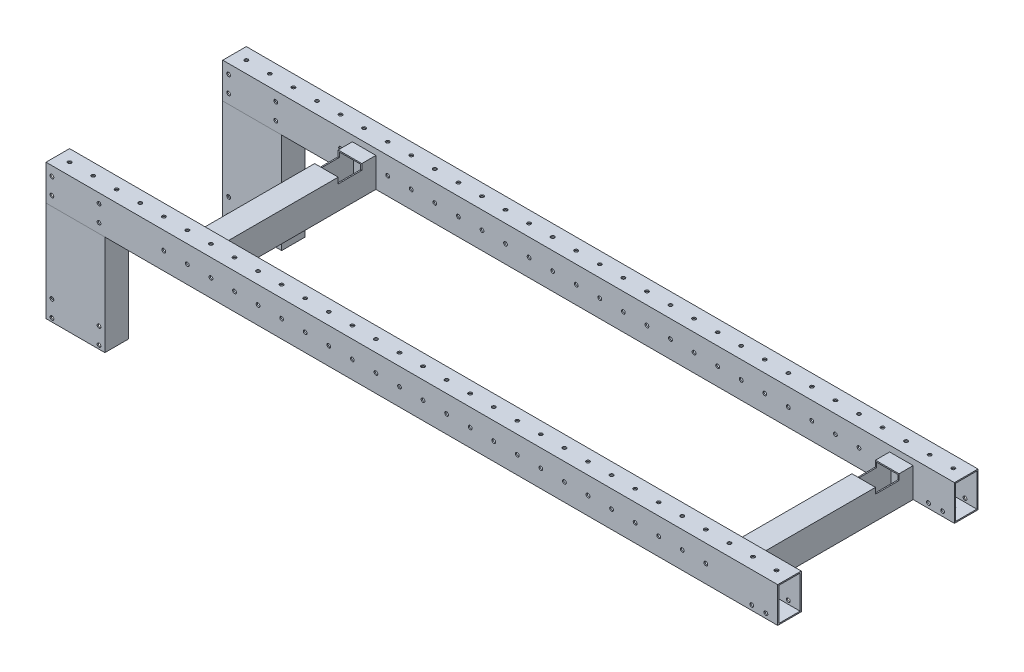
SolidWorks part; units mm, degrees
material "6061-T6 (SS)"
ref_plane "前视基准面" through (0, 0, 0) normal (0, 0, 1) x (1, 0, 0)
ref_plane "上视基准面" through (0, 0, 0) normal (0, 1, 0) x (1, 0, 0)
ref_plane "右视基准面" through (0, 0, 0) normal (1, 0, 0) x (0, 0, -1)
sketch3d "3D草图1"
  line L0 (0, 0, -179.0514) -> (0, 0, 210.5605) construction
  line L1 (-429.4613, 0, 0) -> (512.3941, 0, 0) construction
  line L2 (0, 0, 75) -> (621, 0, 75)
  line L3 (120, 0, 75) -> (120, 0, -75) construction
  line L4 (0, 0, -75) -> (621, 0, -75)
  point P12 (120, 0, 0)
  dimension "D1" = 621
  dimension "D2" = 150
other "方形管 20 X 20 X 2(1)"
ref_plane "基准面1" through (0, 0, 75) normal (1, 0, 0) x (0, 0, -1)
sketch "Sketch1" plane through (0, 0, 75) normal (1, 0, 0) x (0, 0, -1)
  line L0 (9, 14) -> (9, -14)
  line L1 (10, 15) -> (-10, 15)
  line L2 (10, 15) -> (10, -15)
  line L3 (10, -15) -> (-10, -15)
  line L4 (-10, 15) -> (-10, -15)
  line L5 (10, 15) -> (-10, -15) construction
  line L6 (10, -15) -> (-10, 15) construction
  line L7 (9, -14) -> (-9, -14)
  line L8 (-9, 14) -> (-9, -14)
  line L9 (9, 14) -> (-9, 14)
  point P0 (0, 0)
  dimension "D1" = 1
  dimension "D2" = 20
  dimension "D3" = 30
sketch "草图3" plane through (0, 0, 85) normal (0, 0, 1) x (1, 0, 0)
  line L0 (621, 0) -> (529.9491, 0) construction
  line L1 (621, 15) -> (621, -15) construction
  line L2 (5, 7) -> (45, 7) construction
  line L3 (25, 7) -> (25, -12.2961) construction
  line L4 (0, -15) -> (0, 15) construction
  circle A0 centre (45, 7) radius 1.6
  circle A1 centre (5, 7) radius 1.6
  circle A2 centre (45, -7) radius 1.6
  circle A3 centre (5, -7) radius 1.6
  dimension "D1" = 3.2
  dimension "D2" = 14
  dimension "D3" = 25
  dimension "D4" = 40
extrude "切除-拉伸1" cut sketch "草图3" against normal through all
sketch "草图5" plane through (0, 15, 0) normal (0, 1, 0) x (1, 0, 0)
  line L0 (684.2067, 0) -> (-96.6882, 0) construction
  line L1 (0, -75) -> (130.4676, -75) construction
  line L2 (0, -65) -> (0, -85) construction
  line L3 (10, 75) -> (30, 75) construction
  circle A0 centre (10, -75) radius 1.5
  circle A1 centre (10, 75) radius 1.5
  circle A2 centre (30, 75) radius 1.5
  circle A3 centre (30, -75) radius 1.5
  circle A4 centre (50, 75) radius 1.5
  circle A5 centre (50, -75) radius 1.5
  circle A6 centre (70, 75) radius 1.5
  circle A7 centre (70, -75) radius 1.5
  circle A8 centre (90, 75) radius 1.5
  circle A9 centre (90, -75) radius 1.5
  circle A10 centre (110, 75) radius 1.5
  circle A11 centre (110, -75) radius 1.5
  circle A12 centre (130, 75) radius 1.5
  circle A13 centre (130, -75) radius 1.5
  circle A14 centre (150, 75) radius 1.5
  circle A15 centre (150, -75) radius 1.5
  circle A16 centre (170, 75) radius 1.5
  circle A17 centre (170, -75) radius 1.5
  circle A18 centre (190, 75) radius 1.5
  circle A19 centre (190, -75) radius 1.5
  circle A20 centre (210, 75) radius 1.5
  circle A21 centre (210, -75) radius 1.5
  circle A22 centre (230, 75) radius 1.5
  circle A23 centre (230, -75) radius 1.5
  circle A24 centre (250, 75) radius 1.5
  circle A25 centre (250, -75) radius 1.5
  circle A26 centre (270, 75) radius 1.5
  circle A27 centre (270, -75) radius 1.5
  circle A28 centre (290, 75) radius 1.5
  circle A29 centre (290, -75) radius 1.5
  circle A30 centre (310, 75) radius 1.5
  circle A31 centre (310, -75) radius 1.5
  circle A32 centre (330, 75) radius 1.5
  circle A33 centre (330, -75) radius 1.5
  circle A34 centre (350, 75) radius 1.5
  circle A35 centre (350, -75) radius 1.5
  circle A36 centre (370, 75) radius 1.5
  circle A37 centre (370, -75) radius 1.5
  circle A38 centre (390, 75) radius 1.5
  circle A39 centre (390, -75) radius 1.5
  circle A40 centre (410, 75) radius 1.5
  circle A41 centre (410, -75) radius 1.5
  circle A42 centre (430, 75) radius 1.5
  circle A43 centre (430, -75) radius 1.5
  circle A44 centre (450, 75) radius 1.5
  circle A45 centre (450, -75) radius 1.5
  circle A46 centre (470, 75) radius 1.5
  circle A47 centre (470, -75) radius 1.5
  circle A48 centre (490, 75) radius 1.5
  circle A49 centre (490, -75) radius 1.5
  circle A50 centre (510, 75) radius 1.5
  circle A51 centre (510, -75) radius 1.5
  circle A52 centre (530, 75) radius 1.5
  circle A53 centre (530, -75) radius 1.5
  circle A54 centre (550, 75) radius 1.5
  circle A55 centre (550, -75) radius 1.5
  circle A56 centre (570, 75) radius 1.5
  circle A57 centre (570, -75) radius 1.5
  circle A58 centre (590, 75) radius 1.5
  circle A59 centre (590, -75) radius 1.5
  circle A60 centre (610, 75) radius 1.5
  circle A61 centre (610, -75) radius 1.5
  dimension "D1" = 3
  dimension "D2" = 10
  dimension "D4" = 20
  dimension "D3" = 31
extrude "切除-拉伸3" cut sketch "草图5" against normal through all
sketch "草图6" plane through (0, 0, 85) normal (0, 0, 1) x (1, 0, 0)
  line L0 (5, 7) -> (45, 7) construction
  line L1 (25, 7) -> (25, 0) construction
  line L3 (25, 0) -> (621, 0) construction
  line L4 (621, 15) -> (621, -15) construction
  line L5 (25, 0) -> (620.6369, -20.8001) construction
  line L6 (25.5238, 15) -> (621.1607, -5.8001) construction
  line L7 (25.5238, 15) -> (24.4762, -15) construction
  line L8 (621.1607, -5.8001) -> (620.1131, -35.8001) construction
  line L9 (24.4762, -15) -> (620.1131, -35.8001) construction
  line L10 (25.5238, 15) -> (620.1131, -35.8001) construction
  line L11 (621.1607, -5.8001) -> (24.4762, -15) construction
  line L12 (25, 0) -> (620.9092, -10.4016) construction
  circle A0 centre (611, 0) radius 1.6 construction
  circle A1 centre (599, 0) radius 1.6 construction
  circle A2 centre (599, -11) radius 1.6
  circle A3 centre (611, -11) radius 1.6
  point P11 (322.8185, -10.4001)
  dimension "D4" = 3.2
  dimension "D7" = 4
  dimension "D1" = 2
  dimension "D2" = 30
  dimension "D3" = 1
  dimension "D5" = 10
  dimension "D6" = 12
sketch "草图8" plane through (0, 0, 65) normal (0, 0, -1) x (-1, 0, 0)
  line L0 (-621, -15) -> (0, -15) construction
  line L1 (-586, 10) -> (-566, 10)
  line L2 (-586, 10) -> (-586, -15)
  line L3 (-586, -15) -> (-566, -15)
  line L4 (-566, 10) -> (-566, -15)
  line L5 (-586, 10) -> (-566, -15) construction
  line L6 (-586, -15) -> (-566, 10) construction
  line L7 (-585, 9) -> (-567, 9)
  line L8 (-567, 9) -> (-567, -14)
  line L9 (-585, -14) -> (-567, -14)
  line L10 (-585, 9) -> (-585, -14)
  line L11 (-621, -15) -> (-621, 15) construction
  point P0 (-576, -2.5)
  dimension "D1" = 25
  dimension "D2" = 20
  dimension "D4" = 35
  dimension "D3" = 1
extrude "凸台-拉伸1" add sketch "草图8" along normal up to next separate body
sketch "草图9" plane through (586, 0, 0) normal (1, 0, 0) x (0, 0, -1)
  line L0 (65, 10) -> (-65, 10) construction
  line L1 (33, 5) -> (53, 5)
  line L2 (33, 5) -> (33, 10)
  line L3 (33, 10) -> (53, 10)
  line L4 (53, 5) -> (53, 10)
  line L5 (33, 5) -> (53, 10) construction
  line L6 (33, 10) -> (53, 5) construction
  line L7 (65, 10) -> (65, -15) construction
  point P0 (43, 7.5)
  dimension "D1" = 22
  dimension "D2" = 20
  dimension "D3" = 5
extrude "切除-拉伸4" cut sketch "草图9" against normal up to surface (20 mm away) up to face at (566, -2.5, 0)
extrude "切除-拉伸5" cut sketch "草图6" against normal through all
sketch "草图10" plane through (0, -15, 0) normal (0, -1, 0) x (1, 0, 0)
  line L0 (621, 65) -> (0, 65) construction
  line L1 (0, 85) -> (50, 85)
  line L2 (0, 85) -> (0, 65)
  line L3 (0, 65) -> (50, 65)
  line L4 (50, 85) -> (50, 65)
  line L5 (1, 84) -> (1, 66)
  line L6 (1, 66) -> (49, 66)
  line L7 (49, 84) -> (49, 66)
  line L8 (1, 84) -> (49, 84)
  dimension "D1" = 50
  dimension "D2" = 1
extrude "凸台-拉伸2" add sketch "草图10" along normal blind 85 separate body
sketch "草图11" plane through (0, 0, 85) normal (0, 0, 1) x (1, 0, 0)
  line L0 (25, -100) -> (25, -15) construction
  line L1 (50, -100) -> (0, -100) construction
  line L2 (621, -15) -> (0, -15) construction
  line L3 (0, -90) -> (50, -90) construction
  line L4 (0, -100) -> (0, -15) construction
  line L5 (50, -100) -> (50, -15) construction
  line L6 (0, 0) -> (60.7939, 0) construction
  line L7 (0, 15) -> (0, -15) construction
  circle A0 centre (45, -83) radius 1.6
  circle A1 centre (45, -97) radius 1.6
  circle A2 centre (5, -97) radius 1.6
  circle A3 centre (5, -83) radius 1.6
  dimension "D2" = 40
  dimension "D4" = 3.2
  dimension "D1" = 10
  dimension "D3" = 14
extrude "切除-拉伸6" cut sketch "草图11" against normal through all
mirror "镜向1" about plane through (0, 0, 0) normal (0, 0, 1) of bodies 120
pattern_linear "阵列(线性)1" count 2 spacing 456 along (-1, 0, 0) of bodies 116
sketch "草图12" plane through (0, 0, 85) normal (0, 0, 1) x (1, 0, 0)
  line L0 (0, 0) -> (621, 0) construction
  line L1 (621, 15) -> (621, -15) construction
  line L2 (100, 0) -> (120, 0) construction
  line L3 (0, 15) -> (0, -15) construction
  circle A0 centre (100, 0) radius 1.6
  circle A1 centre (120, 0) radius 1.6
  circle A2 centre (140, 0) radius 1.6
  circle A3 centre (160, 0) radius 1.6
  circle A4 centre (180, 0) radius 1.6
  circle A5 centre (200, 0) radius 1.6
  circle A6 centre (220, 0) radius 1.6
  circle A7 centre (240, 0) radius 1.6
  circle A8 centre (260, 0) radius 1.6
  circle A9 centre (280, 0) radius 1.6
  circle A10 centre (300, 0) radius 1.6
  circle A11 centre (320, 0) radius 1.6
  circle A12 centre (340, 0) radius 1.6
  circle A13 centre (360, 0) radius 1.6
  circle A14 centre (380, 0) radius 1.6
  circle A15 centre (400, 0) radius 1.6
  circle A16 centre (420, 0) radius 1.6
  circle A17 centre (440, 0) radius 1.6
  circle A18 centre (460, 0) radius 1.6
  circle A19 centre (480, 0) radius 1.6
  circle A20 centre (500, 0) radius 1.6
  circle A21 centre (520, 0) radius 1.6
  circle A22 centre (540, 0) radius 1.6
  circle A23 centre (560, 0) radius 1.6
  dimension "D1" = 3.2
  dimension "D3" = 20
  dimension "D4" = 100
  dimension "D2" = 24
extrude "切除-拉伸7" cut sketch "草图12" against normal through all
sketch "草图13" plane through (0, 15, 0) normal (0, 1, 0) x (1, 0, 0)
  line L0 (566, 65) -> (586, 65) construction
  line L1 (566, 65) -> (586, 65) construction
  line L2 (581, 65) -> (571, 65) construction
  line L3 (581, 55) -> (571, 55)
  line L4 (581, 75) -> (571, 75)
  line L5 (110, 65) -> (130, 65) construction
  line L6 (110, 65) -> (130, 65) construction
  line L7 (125, 65) -> (115, 65) construction
  line L8 (125, 56) -> (115, 56)
  line L9 (125, 74) -> (115, 74)
  line L10 (621, 65) -> (0, 65) construction
  line L11 (546, 61) -> (526, 61)
  line L12 (546, 61) -> (546, 65)
  line L13 (546, 65) -> (526, 65)
  line L14 (526, 61) -> (526, 65)
  line L15 (546, 61) -> (526, 65) construction
  line L16 (546, 65) -> (526, 61) construction
  line L17 (566, 33) -> (566, -65) construction
  line L18 (426, 61) -> (426, 65)
  line L19 (426, 61) -> (406, 61)
  line L20 (406, 61) -> (406, 65)
  line L21 (426, 65) -> (406, 65)
  line L22 (306, 61) -> (306, 65)
  line L23 (306, 61) -> (286, 61)
  line L24 (286, 61) -> (286, 65)
  line L25 (306, 65) -> (286, 65)
  line L26 (186, 61) -> (186, 65)
  line L27 (186, 61) -> (166, 61)
  line L28 (166, 61) -> (166, 65)
  line L29 (186, 65) -> (166, 65)
  line L30 (546, 61) -> (426, 61) construction
  line L31 (674.0035, 0) -> (0, 0) construction
  line L32 (621, 85) -> (621, 65) construction
  line L33 (616, 61) -> (606, 61)
  line L34 (616, 61) -> (616, 65)
  line L35 (616, 65) -> (606, 65)
  line L36 (606, 61) -> (606, 65)
  line L37 (616, 61) -> (606, 65) construction
  line L38 (616, 65) -> (606, 61) construction
  line L39 (0, 85) -> (0, 65) construction
  line L40 (30, 61) -> (20, 61)
  line L41 (30, 61) -> (30, 65)
  line L42 (30, 65) -> (20, 65)
  line L43 (20, 61) -> (20, 65)
  line L44 (30, 61) -> (20, 65) construction
  line L45 (30, 65) -> (20, 61) construction
  line L46 (621, 85) -> (0, 85) construction
  line L47 (621, 85) -> (0, 85)
  line L48 (0, 85) -> (0, -85)
  line L49 (621, 85) -> (621, -85)
  line L50 (30, -65) -> (20, -61) construction
  line L51 (30, -61) -> (20, -65) construction
  line L52 (616, -65) -> (606, -61) construction
  line L53 (616, -61) -> (606, -65) construction
  line L54 (546, -61) -> (426, -61) construction
  line L55 (546, -65) -> (526, -61) construction
  line L56 (546, -61) -> (526, -65) construction
  line L57 (110, -65) -> (130, -65) construction
  line L58 (566, -65) -> (586, -65) construction
  line L59 (621, -85) -> (0, -85)
  line L60 (20, -61) -> (20, -65)
  line L61 (30, -65) -> (20, -65)
  line L62 (30, -61) -> (30, -65)
  line L63 (30, -61) -> (20, -61)
  line L64 (606, -61) -> (606, -65)
  line L65 (616, -65) -> (606, -65)
  line L66 (616, -61) -> (616, -65)
  line L67 (616, -61) -> (606, -61)
  line L68 (186, -65) -> (166, -65)
  line L69 (166, -61) -> (166, -65)
  line L70 (186, -61) -> (166, -61)
  line L71 (186, -61) -> (186, -65)
  line L72 (306, -65) -> (286, -65)
  line L73 (286, -61) -> (286, -65)
  line L74 (306, -61) -> (286, -61)
  line L75 (306, -61) -> (306, -65)
  line L76 (426, -65) -> (406, -65)
  line L77 (406, -61) -> (406, -65)
  line L78 (426, -61) -> (406, -61)
  line L79 (426, -61) -> (426, -65)
  line L80 (526, -61) -> (526, -65)
  line L81 (546, -65) -> (526, -65)
  line L82 (546, -61) -> (546, -65)
  line L83 (546, -61) -> (526, -61)
  line L84 (125, -65) -> (115, -65) construction
  line L85 (125, -56) -> (115, -56)
  line L86 (125, -74) -> (115, -74)
  line L87 (581, -65) -> (571, -65) construction
  line L88 (581, -55) -> (571, -55)
  line L89 (581, -75) -> (571, -75)
  line L90 (576, 65) -> (576, 27.064) construction
  line L91 (590, 52) -> (586, 52)
  line L92 (590, 52) -> (590, 40)
  line L93 (590, 40) -> (586, 40)
  line L94 (586, 52) -> (586, 40)
  line L95 (590, 52) -> (586, 40) construction
  line L96 (590, 40) -> (586, 52) construction
  line L97 (562, 40) -> (566, 40)
  line L98 (566, 52) -> (566, 40)
  line L99 (562, 52) -> (566, 52)
  line L100 (562, 52) -> (562, 40)
  line L101 (562, -52) -> (562, -40)
  line L102 (562, -52) -> (566, -52)
  line L103 (566, -52) -> (566, -40)
  line L104 (562, -40) -> (566, -40)
  line L105 (590, -40) -> (586, -40)
  line L106 (586, -52) -> (586, -40)
  line L107 (590, -52) -> (586, -52)
  line L108 (590, -52) -> (590, -40)
  line L109 (134, 52) -> (134, 40)
  line L110 (134, 52) -> (130, 52)
  line L111 (130, 52) -> (130, 40)
  line L112 (134, 40) -> (130, 40)
  line L113 (106, 40) -> (110, 40)
  line L114 (110, 52) -> (110, 40)
  line L115 (106, 52) -> (110, 52)
  line L116 (106, 52) -> (106, 40)
  line L117 (134, -40) -> (130, -40)
  line L118 (130, -52) -> (130, -40)
  line L119 (134, -52) -> (130, -52)
  line L120 (134, -52) -> (134, -40)
  line L121 (106, -52) -> (106, -40)
  line L122 (106, -40) -> (110, -40)
  line L123 (110, -52) -> (110, -40)
  line L124 (106, -52) -> (110, -52)
  line L125 (590, 52) -> (134, 52) construction
  arc A0 (581, 55) -> (581, 75) centre (581, 65) ccw
  circle A1 centre (610, 75) radius 1.5
  circle A2 centre (610, 75) radius 1.5
  circle A3 centre (590, 75) radius 1.5
  circle A4 centre (590, 75) radius 1.5
  circle A5 centre (570, 75) radius 1.5
  circle A6 centre (570, 75) radius 1.5 construction
  circle A7 centre (550, 75) radius 1.5
  circle A8 centre (550, 75) radius 1.5
  circle A9 centre (530, 75) radius 1.5
  circle A10 centre (530, 75) radius 1.5
  circle A11 centre (510, 75) radius 1.5
  circle A12 centre (510, 75) radius 1.5
  circle A13 centre (490, 75) radius 1.5
  circle A14 centre (490, 75) radius 1.5
  circle A15 centre (470, 75) radius 1.5
  circle A16 centre (470, 75) radius 1.5
  circle A17 centre (450, 75) radius 1.5
  circle A18 centre (450, 75) radius 1.5
  circle A19 centre (430, 75) radius 1.5
  circle A20 centre (430, 75) radius 1.5
  circle A21 centre (410, 75) radius 1.5
  circle A22 centre (410, 75) radius 1.5
  circle A23 centre (390, 75) radius 1.5
  circle A24 centre (390, 75) radius 1.5
  circle A25 centre (370, 75) radius 1.5
  circle A26 centre (370, 75) radius 1.5
  circle A27 centre (350, 75) radius 1.5
  circle A28 centre (350, 75) radius 1.5
  circle A29 centre (330, 75) radius 1.5
  circle A30 centre (330, 75) radius 1.5
  circle A31 centre (310, 75) radius 1.5
  circle A32 centre (310, 75) radius 1.5
  circle A33 centre (290, 75) radius 1.5
  circle A34 centre (290, 75) radius 1.5
  circle A35 centre (270, 75) radius 1.5
  circle A36 centre (270, 75) radius 1.5
  circle A37 centre (250, 75) radius 1.5
  circle A38 centre (250, 75) radius 1.5
  circle A39 centre (230, 75) radius 1.5
  circle A40 centre (230, 75) radius 1.5
  circle A41 centre (210, 75) radius 1.5
  circle A42 centre (210, 75) radius 1.5
  circle A43 centre (190, 75) radius 1.5
  circle A44 centre (190, 75) radius 1.5
  circle A45 centre (170, 75) radius 1.5
  circle A46 centre (170, 75) radius 1.5
  circle A47 centre (150, 75) radius 1.5
  circle A48 centre (150, 75) radius 1.5
  circle A49 centre (130, 75) radius 1.5
  circle A50 centre (130, 75) radius 1.5
  circle A51 centre (110, 75) radius 1.5
  circle A52 centre (110, 75) radius 1.5
  circle A53 centre (90, 75) radius 1.5
  circle A54 centre (90, 75) radius 1.5
  circle A55 centre (70, 75) radius 1.5
  circle A56 centre (70, 75) radius 1.5
  circle A57 centre (50, 75) radius 1.5
  circle A58 centre (50, 75) radius 1.5
  circle A59 centre (30, 75) radius 1.5
  circle A60 centre (30, 75) radius 1.5
  circle A61 centre (10, 75) radius 1.5
  circle A62 centre (10, 75) radius 1.5
  circle A63 centre (610, -75) radius 1.5
  circle A64 centre (610, -75) radius 1.5
  circle A65 centre (590, -75) radius 1.5
  circle A66 centre (590, -75) radius 1.5
  circle A67 centre (570, -75) radius 1.5
  circle A68 centre (570, -75) radius 1.5 construction
  circle A69 centre (550, -75) radius 1.5
  circle A70 centre (550, -75) radius 1.5
  circle A71 centre (530, -75) radius 1.5
  circle A72 centre (530, -75) radius 1.5
  circle A73 centre (510, -75) radius 1.5
  circle A74 centre (510, -75) radius 1.5
  circle A75 centre (490, -75) radius 1.5
  circle A76 centre (490, -75) radius 1.5
  circle A77 centre (470, -75) radius 1.5
  circle A78 centre (470, -75) radius 1.5
  circle A79 centre (450, -75) radius 1.5
  circle A80 centre (450, -75) radius 1.5
  circle A81 centre (430, -75) radius 1.5
  circle A82 centre (430, -75) radius 1.5
  circle A83 centre (410, -75) radius 1.5
  circle A84 centre (410, -75) radius 1.5
  circle A85 centre (390, -75) radius 1.5
  circle A86 centre (390, -75) radius 1.5
  circle A87 centre (370, -75) radius 1.5
  circle A88 centre (370, -75) radius 1.5
  circle A89 centre (350, -75) radius 1.5
  circle A90 centre (350, -75) radius 1.5
  circle A91 centre (330, -75) radius 1.5
  circle A92 centre (330, -75) radius 1.5
  circle A93 centre (310, -75) radius 1.5
  circle A94 centre (310, -75) radius 1.5
  circle A95 centre (290, -75) radius 1.5
  circle A96 centre (290, -75) radius 1.5
  circle A97 centre (270, -75) radius 1.5
  circle A98 centre (270, -75) radius 1.5
  circle A99 centre (250, -75) radius 1.5
  circle A100 centre (250, -75) radius 1.5
  circle A101 centre (230, -75) radius 1.5
  circle A102 centre (230, -75) radius 1.5
  circle A103 centre (210, -75) radius 1.5
  circle A104 centre (210, -75) radius 1.5
  circle A105 centre (190, -75) radius 1.5
  circle A106 centre (190, -75) radius 1.5
  circle A107 centre (170, -75) radius 1.5
  circle A108 centre (170, -75) radius 1.5
  circle A109 centre (150, -75) radius 1.5
  circle A110 centre (150, -75) radius 1.5
  circle A111 centre (130, -75) radius 1.5
  circle A112 centre (130, -75) radius 1.5
  circle A113 centre (110, -75) radius 1.5
  circle A114 centre (110, -75) radius 1.5
  circle A115 centre (90, -75) radius 1.5
  circle A116 centre (90, -75) radius 1.5
  circle A117 centre (70, -75) radius 1.5
  circle A118 centre (70, -75) radius 1.5
  circle A119 centre (50, -75) radius 1.5
  circle A120 centre (50, -75) radius 1.5
  circle A121 centre (30, -75) radius 1.5
  circle A122 centre (30, -75) radius 1.5
  circle A123 centre (10, -75) radius 1.5
  circle A124 centre (10, -75) radius 1.5
  arc A125 (571, 75) -> (571, 55) centre (571, 65) ccw
  arc A126 (125, 56) -> (125, 74) centre (125, 65) ccw
  arc A127 (115, 74) -> (115, 56) centre (115, 65) ccw
  circle A128 centre (570, -75) radius 1.5 construction
  circle A129 centre (10, -75) radius 1.5
  circle A130 centre (30, -75) radius 1.5
  circle A131 centre (50, -75) radius 1.5
  circle A132 centre (70, -75) radius 1.5
  circle A133 centre (90, -75) radius 1.5
  circle A134 centre (110, -75) radius 1.5
  circle A135 centre (130, -75) radius 1.5
  circle A136 centre (150, -75) radius 1.5
  circle A137 centre (170, -75) radius 1.5
  circle A138 centre (190, -75) radius 1.5
  circle A139 centre (210, -75) radius 1.5
  circle A140 centre (230, -75) radius 1.5
  circle A141 centre (250, -75) radius 1.5
  circle A142 centre (270, -75) radius 1.5
  circle A143 centre (290, -75) radius 1.5
  circle A144 centre (310, -75) radius 1.5
  circle A145 centre (330, -75) radius 1.5
  circle A146 centre (350, -75) radius 1.5
  circle A147 centre (370, -75) radius 1.5
  circle A148 centre (390, -75) radius 1.5
  circle A149 centre (410, -75) radius 1.5
  circle A150 centre (430, -75) radius 1.5
  circle A151 centre (450, -75) radius 1.5
  circle A152 centre (470, -75) radius 1.5
  circle A153 centre (490, -75) radius 1.5
  circle A154 centre (510, -75) radius 1.5
  circle A155 centre (530, -75) radius 1.5
  circle A156 centre (550, -75) radius 1.5
  circle A157 centre (590, -75) radius 1.5
  circle A158 centre (610, -75) radius 1.5
  arc A159 (125, -56) -> (125, -74) centre (125, -65) cw
  arc A160 (115, -74) -> (115, -56) centre (115, -65) cw
  arc A161 (581, -55) -> (581, -75) centre (581, -65) cw
  arc A162 (571, -75) -> (571, -55) centre (571, -65) cw
  point P190 (576, 65)
  point P199 (120, 65)
  point P204 (536, 63)
  point P230 (611, 63)
  point P237 (25, 63)
  point P296 (621, 0)
  point P308 (25, -63)
  point P309 (611, -63)
  point P310 (536, -63)
  point P313 (120, -65)
  point P320 (576, -65)
  point P325 (588, 46)
  dimension "D63" = 20
  dimension "D64" = 10
  dimension "D65" = 18
  dimension "D66" = 10
  dimension "D67" = 4
  dimension "D68" = 20
  dimension "D69" = 20
  dimension "D71" = 120
  dimension "D72" = 10
  dimension "D73" = 5
  dimension "D74" = 10
  dimension "D75" = 20
  dimension "D76" = 4
  dimension "D77" = 12
  dimension "D78" = 40
  dimension "D79" = 2
  dimension "D80" = 456
  dimension "D1" = 0
  dimension "D2" = 0
  dimension "D3" = 0
  dimension "D4" = 0
  dimension "D5" = 0
  dimension "D6" = 0
  dimension "D7" = 0
  dimension "D8" = 0
  dimension "D9" = 0
  dimension "D10" = 0
  dimension "D11" = 0
  dimension "D12" = 0
  dimension "D13" = 0
  dimension "D14" = 0
  dimension "D15" = 0
  dimension "D16" = 0
  dimension "D17" = 0
  dimension "D18" = 0
  dimension "D19" = 0
  dimension "D20" = 0
  dimension "D21" = 0
  dimension "D22" = 0
  dimension "D23" = 0
  dimension "D24" = 0
  dimension "D25" = 0
  dimension "D26" = 0
  dimension "D27" = 0
  dimension "D28" = 0
  dimension "D29" = 0
  dimension "D30" = 0
  dimension "D31" = 0
  dimension "D32" = 0
  dimension "D33" = 0
  dimension "D34" = 0
  dimension "D35" = 0
  dimension "D36" = 0
  dimension "D37" = 0
  dimension "D38" = 0
  dimension "D39" = 0
  dimension "D40" = 0
  dimension "D41" = 0
  dimension "D42" = 0
  dimension "D43" = 0
  dimension "D44" = 0
  dimension "D45" = 0
  dimension "D46" = 0
  dimension "D47" = 0
  dimension "D48" = 0
  dimension "D49" = 0
  dimension "D50" = 0
  dimension "D51" = 0
  dimension "D52" = 0
  dimension "D53" = 0
  dimension "D54" = 0
  dimension "D55" = 0
  dimension "D56" = 0
  dimension "D57" = 0
  dimension "D58" = 0
  dimension "D59" = 0
  dimension "D60" = 0
  dimension "D61" = 0
  dimension "D62" = 0
  dimension "D70" = 4
extrude "凸台-拉伸3" [suppressed] add sketch "草图13" along normal blind 2 separate body
sketch "草图14" [suppressed] plane through (0, 0, 85) normal (0, 0, 1) x (1, 0, 0)
  line L0 (0, -100) -> (50, -100)
  line L1 (50, -100) -> (135, -15)
  line L2 (621, -15) -> (0, -15) construction
  line L3 (135, -15) -> (135, 15)
  line L4 (0, 15) -> (621, 15) construction
  line L5 (135, 15) -> (0, 15)
  line L6 (0, 15) -> (0, -100)
  line L7 (50, -15) -> (0, -15) construction
  line L8 (-10, 0) -> (60, 0)
  line L9 (-10, 0) -> (-10, -30)
  line L10 (-10, -30) -> (60, -30)
  line L11 (60, 0) -> (60, -30)
  line L12 (-10, 0) -> (60, -30) construction
  line L13 (-10, -30) -> (60, 0) construction
  line L14 (0, 15) -> (-15, 0)
  line L15 (-15, 0) -> (-15, -30)
  line L16 (-15, -30) -> (0, -45)
  circle A0 centre (5, 7) radius 1.6 construction
  circle A1 centre (5, 7) radius 1.6
  circle A2 centre (45, 7) radius 1.6 construction
  circle A3 centre (45, 7) radius 1.6
  circle A4 centre (5, -97) radius 1.6 construction
  circle A5 centre (5, -97) radius 1.6
  circle A6 centre (45, -97) radius 1.6 construction
  circle A7 centre (45, -97) radius 1.6
  circle A8 centre (120, 0) radius 1.6 construction
  circle A9 centre (120, 0) radius 1.6
  point P27 (25, -15)
  circle M12 centre (5, -83) radius 1.6
  circle M13 centre (5, -97) radius 1.6
  circle M14 centre (45, -97) radius 1.6
  circle M15 centre (45, -83) radius 1.6
  line M17 (0, -15) -> (0, -100)
  line M18 (0, -100) -> (50, -100)
  line M19 (50, -100) -> (50, -15)
  dimension "D1" = 45
  dimension "D2" = 70
  dimension "D3" = 30
  dimension "D4" = 45
  dimension "D5" = 45
extrude "凸台-拉伸4" [suppressed] add sketch "草图14" along normal blind 2 separate body contours L8 L11 L10 L1 L3 L5 L6 A9 A3 A1 M19 | L10 L6 M17 M18 M19 M13 M15 M14 M12 | L15 L16 L6 L10 L9 L8 L14
